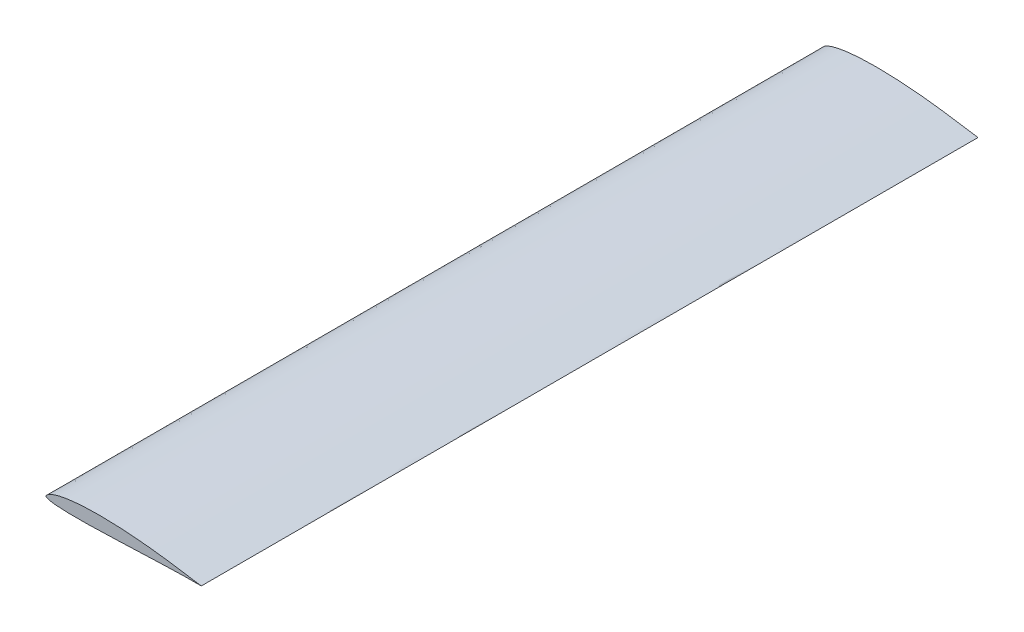
SolidWorks part; units mm, degrees
material "EPP"
ref_plane "Front Plane" through (0, 0, 0) normal (0, 0, 1) x (1, 0, 0)
ref_plane "Top Plane" through (0, 0, 0) normal (0, 1, 0) x (1, 0, 0)
ref_plane "Right Plane" through (0, 0, 0) normal (1, 0, 0) x (0, 0, -1)
curve "Curve1"
  spline degree 3 poles (49.6515, 0.009, 0) (50.0884, -0.0053, 0) (49.6522, 0.033, 0) (49.3011, 0.0832, 0) (48.4593, 0.1945, 0) (47.4415, 0.3499, 0) (46.1338, 0.5549, 0) (44.6155, 0.7993, 0) (42.8923, 1.0751, 0) (40.9958, 1.371, 0) (38.9477, 1.6747, 0) (36.7703, 1.9711, 0) (34.4838, 2.2498, 0) (32.109, 2.5048, 0) (29.6686, 2.7322, 0) (27.1889, 2.9318, 0) (24.6971, 3.0996, 0) (22.2188, 3.2252, 0) (19.7784, 3.3048, 0) (17.3996, 3.3388, 0) (15.1043, 3.321, 0) (12.9138, 3.2492, 0) (10.8475, 3.1296, 0) (8.9245, 2.9596, 0) (7.1613, 2.7404, 0) (5.5715, 2.4767, 0) (4.1671, 2.1739, 0) (2.9576, 1.8376, 0) (1.9505, 1.4773, 0) (1.1488, 1.103, 0) (0.5587, 0.7311, 0) (0.2281, 0.4366, 0) (0.09, 0.2394, 0) (0.0408, 0.1522, 0) (0.0104, 0.0738, 0) (-0.0015, 0.012, 0) (0.0009, -0.0367, 0) (0.0247, -0.0804, 0) (0.0694, -0.1305, 0) (0.1411, -0.1885, 0) (0.3144, -0.2962, 0) (0.7005, -0.4536, 0) (1.3781, -0.6282, 0) (2.3375, -0.7877, 0) (3.539, -0.9182, 0) (4.9742, -1.0154, 0) (6.6312, -1.0793, 0) (8.4956, -1.1107, 0) (10.5497, -1.112, 0) (12.7728, -1.0868, 0) (15.1414, -1.0389, 0) (17.6298, -0.9723, 0) (20.2103, -0.8906, 0) (22.8538, -0.7976, 0) (25.5303, -0.6969, 0) (28.2091, -0.5925, 0) (30.859, -0.4876, 0) (33.449, -0.3866, 0) (35.9478, -0.2924, 0) (38.325, -0.208, 0) (40.551, -0.1358, 0) (42.5964, -0.0785, 0) (44.4361, -0.0365, 0) (46.0378, -0.0091, 0) (47.399, 0.0043, 0) (48.4441, 0.0096, 0) (49.2972, 0.0042, 0) (49.6515, 0.009, 0) (50.0884, -0.0053, 0) (49.6522, 0.033, 0) knots -0.014204 -0.006419 -0.001632 0 0.001631 0.006435 0.014221 0.024766 0.037827 0.053149 0.070474 0.089536 0.110075 0.13186 0.154693 0.178371 0.20268 0.227364 0.252133 0.276728 0.300939 0.324527 0.347267 0.368992 0.389507 0.408628 0.426224 0.442179 0.456396 0.468805 0.479372 0.488086 0.494968 0.500034 0.501036 0.502094 0.502997 0.503513 0.503956 0.504409 0.504955 0.505943 0.50713 0.510998 0.518232 0.527846 0.539809 0.554056 0.57049 0.588974 0.609342 0.631393 0.654894 0.67959 0.705203 0.731447 0.75802 0.78462 0.810936 0.836657 0.861473 0.885081 0.907188 0.927507 0.945765 0.961712 0.975122 0.985796 0.993581 0.998368 1 1.001631 1.006435 1.014221 periodic
sketch "Sketch1" plane through (0, 0, 0) normal (0, 0, 1) x (1, 0, 0)
  spline S0 degree 3 poles (49.6515, 0.009) (50.0884, -0.0053) (49.6522, 0.033) (49.3011, 0.0832) (48.4593, 0.1945) (47.4415, 0.3499) (46.1338, 0.5549) (44.6155, 0.7993) (42.8923, 1.0751) (40.9958, 1.371) (38.9477, 1.6747) (36.7703, 1.9711) (34.4838, 2.2498) (32.109, 2.5048) (29.6686, 2.7322) (27.1889, 2.9318) (24.6971, 3.0996) (22.2188, 3.2252) (19.7784, 3.3048) (17.3996, 3.3388) (15.1043, 3.321) (12.9138, 3.2492) (10.8475, 3.1296) (8.9245, 2.9596) (7.1613, 2.7404) (5.5715, 2.4767) (4.1671, 2.1739) (2.9576, 1.8376) (1.9505, 1.4773) (1.1488, 1.103) (0.5587, 0.7311) (0.2281, 0.4366) (0.09, 0.2394) (0.0408, 0.1522) (0.0104, 0.0738) (-0.0015, 0.012) (0.0009, -0.0367) (0.0247, -0.0804) (0.0694, -0.1305) (0.1411, -0.1885) (0.3144, -0.2962) (0.7005, -0.4536) (1.3781, -0.6282) (2.3375, -0.7877) (3.539, -0.9182) (4.9742, -1.0154) (6.6312, -1.0793) (8.4956, -1.1107) (10.5497, -1.112) (12.7728, -1.0868) (15.1414, -1.0389) (17.6298, -0.9723) (20.2103, -0.8906) (22.8538, -0.7976) (25.5303, -0.6969) (28.2091, -0.5925) (30.859, -0.4876) (33.449, -0.3866) (35.9478, -0.2924) (38.325, -0.208) (40.551, -0.1358) (42.5964, -0.0785) (44.4361, -0.0365) (46.0378, -0.0091) (47.399, 0.0043) (48.4441, 0.0096) (49.2972, 0.0042) (49.6515, 0.009) (50.0884, -0.0053) (49.6522, 0.033) knots -0.014204 -0.006419 -0.001632 0 0.001631 0.006435 0.014221 0.024766 0.037827 0.053149 0.070474 0.089536 0.110075 0.13186 0.154693 0.178371 0.20268 0.227364 0.252133 0.276728 0.300939 0.324527 0.347267 0.368992 0.389507 0.408628 0.426224 0.442179 0.456396 0.468805 0.479372 0.488086 0.494968 0.500034 0.501036 0.502094 0.502997 0.503513 0.503956 0.504409 0.504955 0.505943 0.50713 0.510998 0.518232 0.527846 0.539809 0.554056 0.57049 0.588974 0.609342 0.631393 0.654894 0.67959 0.705203 0.731447 0.75802 0.78462 0.810936 0.836657 0.861473 0.885081 0.907188 0.927507 0.945765 0.961712 0.975122 0.985796 0.993581 0.998368 1 1.001631 1.006435 1.014221 only from (50, 0) to (50, 0) construction
  spline S1 degree 3 poles (49.6515, 0.009) (50.0884, -0.0053) (49.6522, 0.033) (49.3011, 0.0832) (48.4593, 0.1945) (47.4415, 0.3499) (46.1338, 0.5549) (44.6155, 0.7993) (42.8923, 1.0751) (40.9958, 1.371) (38.9477, 1.6747) (36.7703, 1.9711) (34.4838, 2.2498) (32.109, 2.5048) (29.6686, 2.7322) (27.1889, 2.9318) (24.6971, 3.0996) (22.2188, 3.2252) (19.7784, 3.3048) (17.3996, 3.3388) (15.1043, 3.321) (12.9138, 3.2492) (10.8475, 3.1296) (8.9245, 2.9596) (7.1613, 2.7404) (5.5715, 2.4767) (4.1671, 2.1739) (2.9576, 1.8376) (1.9505, 1.4773) (1.1488, 1.103) (0.5587, 0.7311) (0.2281, 0.4366) (0.09, 0.2394) (0.0408, 0.1522) (0.0104, 0.0738) (-0.0015, 0.012) (0.0009, -0.0367) (0.0247, -0.0804) (0.0694, -0.1305) (0.1411, -0.1885) (0.3144, -0.2962) (0.7005, -0.4536) (1.3781, -0.6282) (2.3375, -0.7877) (3.539, -0.9182) (4.9742, -1.0154) (6.6312, -1.0793) (8.4956, -1.1107) (10.5497, -1.112) (12.7728, -1.0868) (15.1414, -1.0389) (17.6298, -0.9723) (20.2103, -0.8906) (22.8538, -0.7976) (25.5303, -0.6969) (28.2091, -0.5925) (30.859, -0.4876) (33.449, -0.3866) (35.9478, -0.2924) (38.325, -0.208) (40.551, -0.1358) (42.5964, -0.0785) (44.4361, -0.0365) (46.0378, -0.0091) (47.399, 0.0043) (48.4441, 0.0096) (49.2972, 0.0042) (49.6515, 0.009) (50.0884, -0.0053) (49.6522, 0.033) knots -0.014204 -0.006419 -0.001632 0 0.001631 0.006435 0.014221 0.024766 0.037827 0.053149 0.070474 0.089536 0.110075 0.13186 0.154693 0.178371 0.20268 0.227364 0.252133 0.276728 0.300939 0.324527 0.347267 0.368992 0.389507 0.408628 0.426224 0.442179 0.456396 0.468805 0.479372 0.488086 0.494968 0.500034 0.501036 0.502094 0.502997 0.503513 0.503956 0.504409 0.504955 0.505943 0.50713 0.510998 0.518232 0.527846 0.539809 0.554056 0.57049 0.588974 0.609342 0.631393 0.654894 0.67959 0.705203 0.731447 0.75802 0.78462 0.810936 0.836657 0.861473 0.885081 0.907188 0.927507 0.945765 0.961712 0.975122 0.985796 0.993581 0.998368 1 1.001631 1.006435 1.014221 only from (50, 0) to (50, 0)
extrude "Boss-Extrude1" add sketch "Sketch1" along normal blind 250
sketch "Sketch2" plane through (0, 0, 0) normal (0, 0, -1) x (-1, 0, 0)
  line L0 (0, 0) -> (-50, 0) construction
  line L2 (-18.473, 1.59) -> (-15.473, 1.59)
  line L3 (-18.473, 1.59) -> (-18.473, 0.59)
  line L4 (-18.473, 0.59) -> (-15.473, 0.59)
  line L5 (-15.473, 1.59) -> (-15.473, 0.59)
  line L6 (-18.473, 1.59) -> (-15.473, 0.59) construction
  line L7 (-18.473, 0.59) -> (-15.473, 1.59) construction
  spline S0 degree 3 poles (-49.6522, 0.033) (-50.0884, -0.0053) (-49.6515, 0.009) (-49.2972, 0.0042) (-48.4441, 0.0096) (-47.399, 0.0043) (-46.0378, -0.0091) (-44.4361, -0.0365) (-42.5964, -0.0785) (-40.551, -0.1358) (-38.325, -0.208) (-35.9478, -0.2924) (-33.449, -0.3866) (-30.859, -0.4876) (-28.2091, -0.5925) (-25.5303, -0.6969) (-22.8538, -0.7976) (-20.2103, -0.8906) (-17.6298, -0.9723) (-15.1414, -1.0389) (-12.7728, -1.0868) (-10.5497, -1.112) (-8.4956, -1.1107) (-6.6312, -1.0793) (-4.9742, -1.0154) (-3.539, -0.9182) (-2.3375, -0.7877) (-1.3781, -0.6282) (-0.7005, -0.4536) (-0.3144, -0.2962) (-0.1411, -0.1885) (-0.0694, -0.1305) (-0.0247, -0.0804) (-0.0009, -0.0367) (0.0015, 0.012) (-0.0104, 0.0738) (-0.0408, 0.1522) (-0.09, 0.2394) (-0.2281, 0.4366) (-0.5587, 0.7311) (-1.1488, 1.103) (-1.9505, 1.4773) (-2.9576, 1.8376) (-4.1671, 2.1739) (-5.5715, 2.4767) (-7.1613, 2.7404) (-8.9245, 2.9596) (-10.8475, 3.1296) (-12.9138, 3.2492) (-15.1043, 3.321) (-17.3996, 3.3388) (-19.7784, 3.3048) (-22.2188, 3.2252) (-24.6971, 3.0996) (-27.1889, 2.9318) (-29.6686, 2.7322) (-32.109, 2.5048) (-34.4838, 2.2498) (-36.7703, 1.9711) (-38.9477, 1.6747) (-40.9958, 1.371) (-42.8923, 1.0751) (-44.6155, 0.7993) (-46.1338, 0.5549) (-47.4415, 0.3499) (-48.4593, 0.1945) (-49.3011, 0.0832) (-49.6522, 0.033) (-50.0884, -0.0053) (-49.6515, 0.009) knots -0.014221 -0.006435 -0.001631 0 0.001632 0.006419 0.014204 0.024878 0.038288 0.054235 0.072493 0.092812 0.114919 0.138527 0.163343 0.189064 0.21538 0.24198 0.268553 0.294797 0.32041 0.345106 0.368607 0.390658 0.411026 0.42951 0.445944 0.460191 0.472154 0.481768 0.489002 0.49287 0.494057 0.495045 0.495591 0.496044 0.496487 0.497003 0.497906 0.498964 0.499966 0.505032 0.511914 0.520628 0.531195 0.543604 0.557821 0.573776 0.591372 0.610493 0.631008 0.652733 0.675473 0.699061 0.723272 0.747867 0.772636 0.79732 0.821629 0.845307 0.86814 0.889925 0.910464 0.929526 0.946851 0.962173 0.975234 0.985779 0.993565 0.998369 1 1.001632 1.006419 1.014204 only from (-50, 0) to (-50, 0) construction
  point P4 (-16.973, 1.09)
  dimension "D1" = 3
  dimension "D2" = 1
  dimension "D3" = 1.59
  dimension "D4" = 31.527
extrude "Boss-Extrude2" add sketch "Sketch2" along normal blind 1
